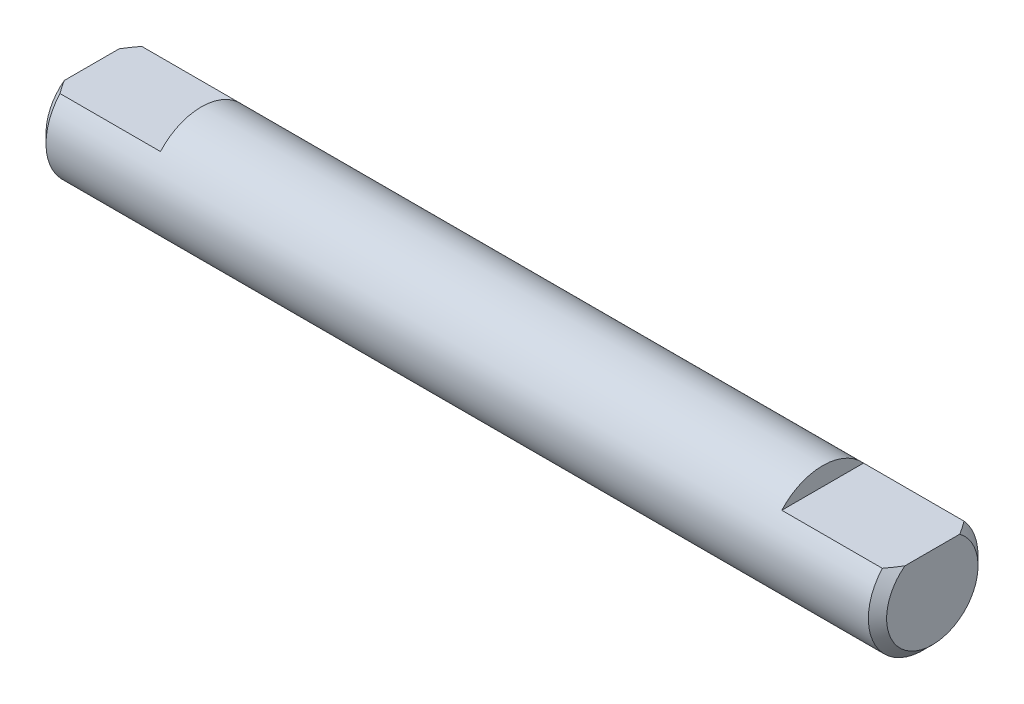
SolidWorks part; units mm, degrees
material "Wrought Stainless Steel"
ref_plane "Front Plane" through (0, 0, 0) normal (0, 0, 1) x (1, 0, 0)
ref_plane "Top Plane" through (0, 0, 0) normal (0, 1, 0) x (1, 0, 0)
ref_plane "Right Plane" through (0, 0, 0) normal (1, 0, 0) x (0, 0, -1)
sketch "Sketch1" plane through (0, 0, 0) normal (1, 0, 0) x (0, 0, -1)
  circle A0 centre (0, 0) radius 3
  dimension "D1" = 6
extrude "Boss-Extrude1" add sketch "Sketch1" along normal mid plane 46
sketch "Sketch2" plane through (23, 0, 0) normal (1, 0, 0) x (0, 0, -1)
  line L0 (-2.2361, 2) -> (2.2361, 2)
  arc A0 (2.2361, 2) -> (-2.2361, 2) centre (0, 0) ccw
  dimension "D2" = 6
  dimension "D1" = 2
extrude "Cut-Extrude1" cut sketch "Sketch2" against normal blind 6
mirror "Mirror1" about plane through (0, 0, 0) normal (1, 0, 0) of "Cut-Extrude1"
chamfer "Chamfer1" distance 0.5 angle 45 2 edges at (-23, -3, 0) (23, -3, 0)
